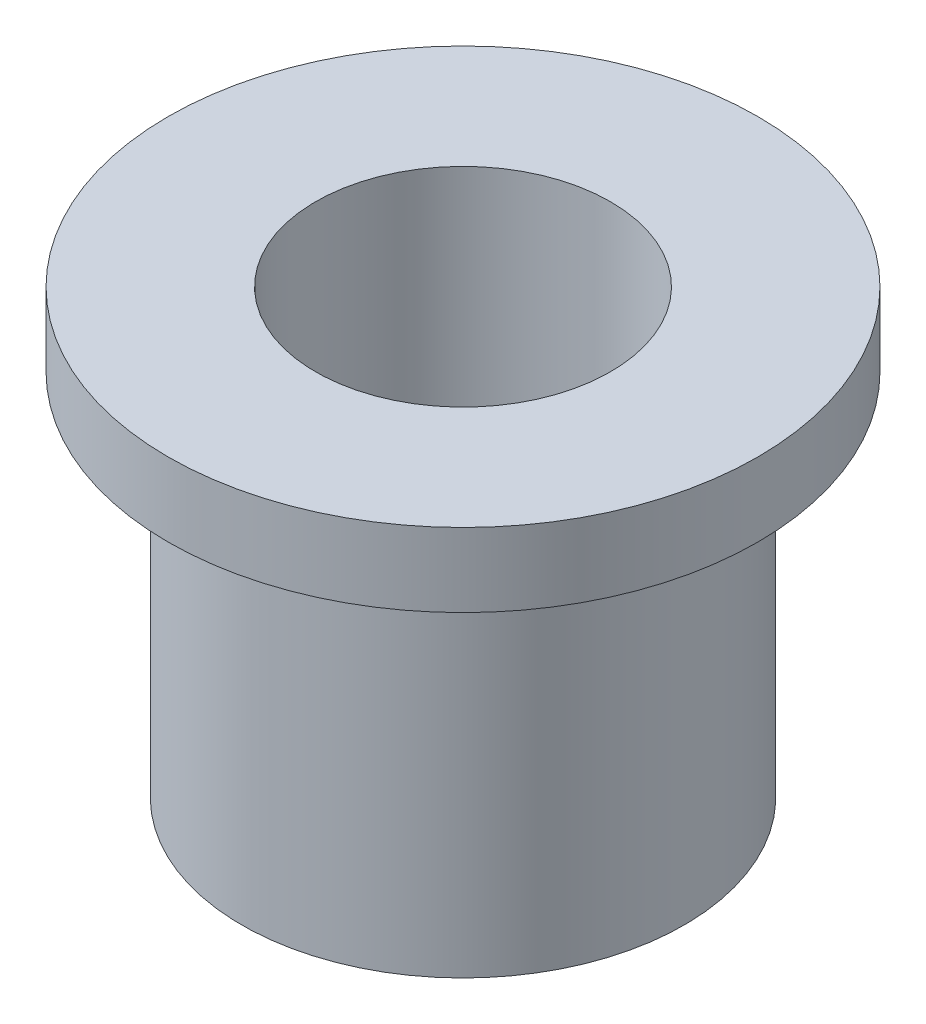
SolidWorks part; units mm, degrees
material "Nylon 101"
ref_plane "Front Plane" through (0, 0, 0) normal (0, 0, 1) x (1, 0, 0)
ref_plane "Top Plane" through (0, 0, 0) normal (0, 1, 0) x (1, 0, 0)
ref_plane "Right Plane" through (0, 0, 0) normal (1, 0, 0) x (0, 0, -1)
sketch "Sketch1" plane through (0, 0, 0) normal (1, 0, 0) x (0, 0, -1)
  line L0 (0, 0) -> (0, 9.1228) construction
  line L1 (3.175, 0) -> (3.175, 9.525)
  line L2 (3.175, 9.525) -> (6.35, 9.525)
  line L3 (6.35, 9.525) -> (6.35, 7.9375)
  line L4 (6.35, 7.9375) -> (4.7625, 7.9375)
  line L5 (4.7625, 7.9375) -> (4.7625, 0)
  line L6 (4.7625, 0) -> (3.175, 0)
  dimension "D1" = 3.175
  dimension "D2" = 1.5875
  dimension "D3" = 9.525
  dimension "D4" = 6.35
  dimension "D5" = 9.525
revolve "Revolve1" add sketch "Sketch1" angle 360 about L0
